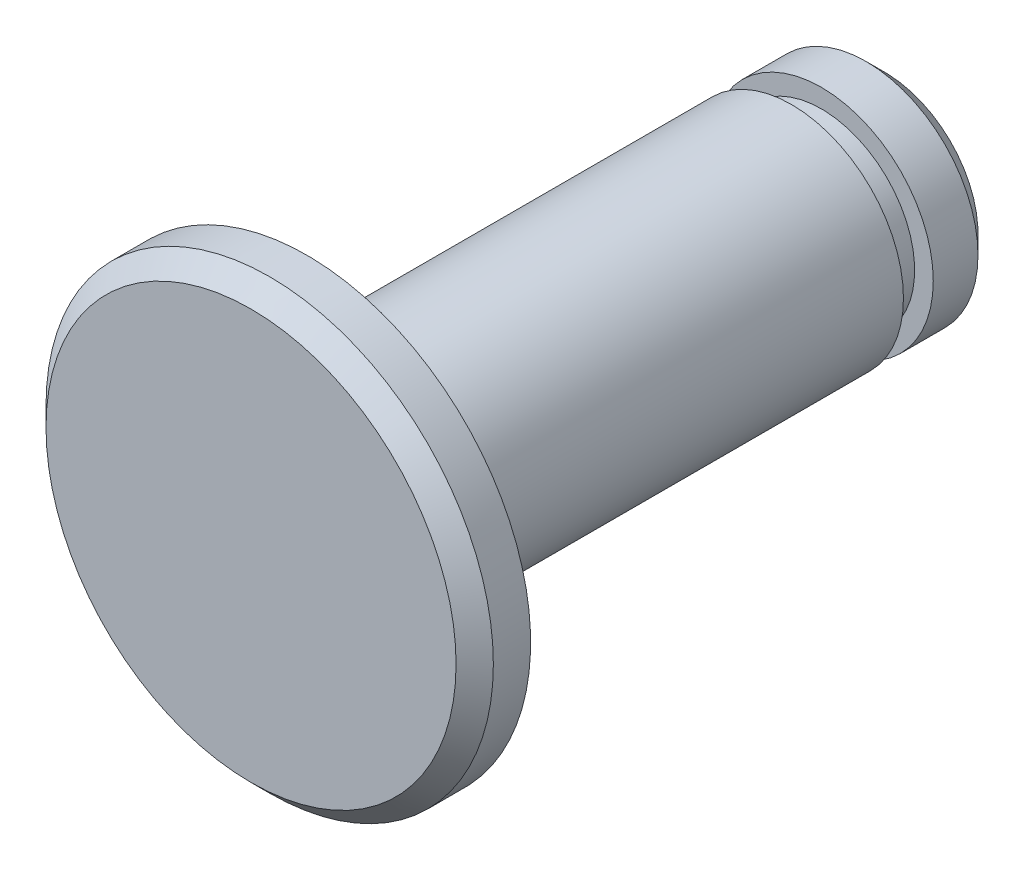
SolidWorks part; units mm, degrees
ref_plane "Front Plane" through (0, 0, 0) normal (0, 0, 1) x (1, 0, 0)
ref_plane "Top Plane" through (0, 0, 0) normal (0, 1, 0) x (1, 0, 0)
ref_plane "Right Plane" through (0, 0, 0) normal (1, 0, 0) x (0, 0, -1)
sketch "Sketch1" plane through (0, 0, 0) normal (0, 1, 0) x (1, 0, 0)
  line L0 (0, 21.2761) -> (0, -51.3839) construction
  line L1 (0, -22.3747) -> (-6, -22.3747)
  line L2 (-6, -22.3747) -> (-6, -20.8747)
  line L3 (-6, -20.8747) -> (-3, -20.8747)
  line L4 (-3, -20.8747) -> (-3, -7.8747)
  line L5 (-3, -7.8747) -> (-2.5, -7.8747)
  line L6 (-2.5, -7.8747) -> (-2.5, -7.0747)
  line L7 (-2.5, -7.0747) -> (-3, -7.0747)
  line L8 (-3, -7.0747) -> (-3, -5.3747)
  line L9 (-3, -5.3747) -> (0, -5.3747)
  line L10 (0, 21.2761) -> (0, 37.7351) construction
  line L11 (0, -5.3747) -> (0, -22.3747)
  dimension "D1" = 0.5
  dimension "D2" = 3
  dimension "D3" = 3
  dimension "D4" = 6
  dimension "D5" = 1.5
  dimension "D6" = 13
  dimension "D7" = 0.8
  dimension "D8" = 17
revolve "Revolve1" add sketch "Sketch1" angle 360 about L0
chamfer "Chamfer1" distance 0.5 angle 45 2 edges at (-3, 0, 5.3747) (-6, 0, 22.3747)
